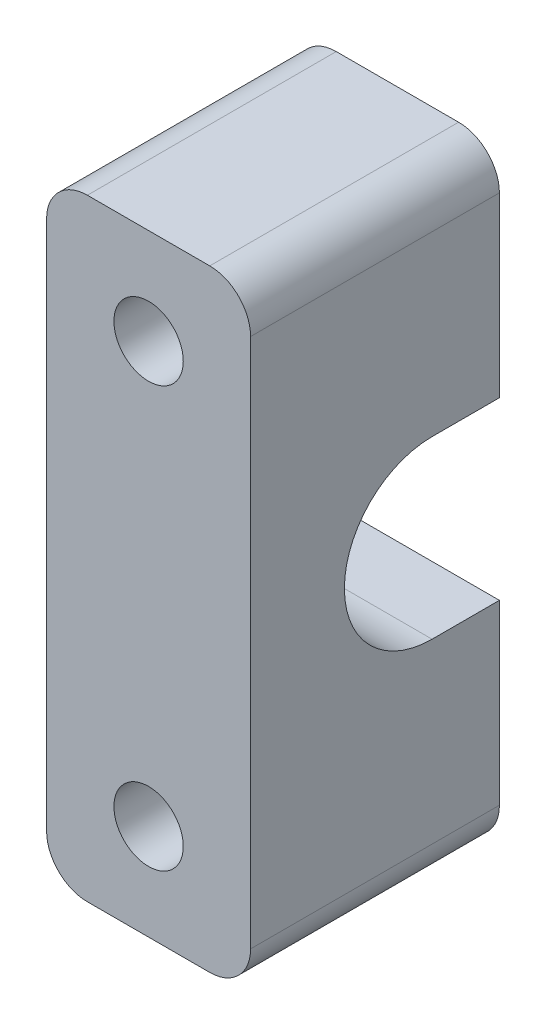
SolidWorks part; units mm, degrees
ref_plane "Front Plane" through (0, 0, 0) normal (0, 0, 1) x (1, 0, 0)
ref_plane "Top Plane" through (0, 0, 0) normal (0, 1, 0) x (1, 0, 0)
ref_plane "Right Plane" through (0, 0, 0) normal (1, 0, 0) x (0, 0, -1)
sketch "Sketch1" plane through (0, 0, 0) normal (1, 0, 0) x (0, 0, -1)
  line L1 (-6.1, -15) -> (6.1, -15)
  line L2 (-6.1, -15) -> (-6.1, 15)
  line L3 (-6.1, 15) -> (6.1, 15)
  line L4 (6.1, -15) -> (6.1, 15)
  line L5 (-6.1, -15) -> (6.1, 15) construction
  line L6 (-6.1, 15) -> (6.1, -15) construction
  point P0 (0, 0)
  dimension "D2" = 30
  dimension "D3" = 12.2
extrude "Boss-Extrude1" add sketch "Sketch1" along normal mid plane 10
sketch "Sketch5" plane through (5, 0, 0) normal (1, 0, 0) x (0, 0, -1)
  line L0 (25.0671, 0) -> (-25.0671, 0) construction
  line L1 (6.1, -15) -> (6.1, 15) construction
  circle A0 centre (2.8, 0) radius 4.3
  dimension "D1" = 8.6
  dimension "D2" = 3.3
extrude "Cut-Extrude2" cut sketch "Sketch5" against normal blind 7
sketch "Sketch3" plane through (0, 0, 6.1) normal (0, 0, 1) x (1, 0, 0)
  line L0 (0, -25.131) -> (0, 25.131) construction
  line L1 (25.0671, 0) -> (-25.0671, 0) construction
  circle A0 centre (0, 10.3) radius 1.7
  dimension "D1" = 3.4
  dimension "D2" = 10.3
extrude "Cut-Extrude1" cut sketch "Sketch3" against normal through all
mirror "Mirror1" about plane through (0, 0, 0) normal (0, 1, 0) of "Cut-Extrude1"
fillet "Fillet1" radius 2 4 edges at (-5, -15, 0) (5, -15, 0) (-5, 15, 0) (5, 15, 0)
fillet "Fillet2" radius 0.1 2 edges at (1.5, 2.7568, -6.1) (1.5, -2.7568, -6.1)
sketch "Sketch6" plane through (5, 0, 0) normal (1, 0, 0) x (0, 0, -1)
  line L0 (2.8, 0) -> (6.1, 0) construction
  line L1 (25.0671, 0) -> (-25.0671, 0) construction
  line L2 (2.8, 4.3) -> (6.1, 4.3)
  line L3 (2.8, -4.3) -> (6.1, -4.3)
  line L4 (6.1, 3.0199) -> (6.1, 13) construction
  arc A0 (2.8, 4.3) -> (2.8, -4.3) centre (2.8, 0) ccw
  arc A1 (6.1, -4.3) -> (6.1, 4.3) centre (6.1, 0) ccw
  arc A2 (5.9273, 2.9513) -> (5.9273, -2.9513) centre (2.8, 0) ccw construction
  point P5 (4.45, 0)
extrude "Cut-Extrude3" cut sketch "Sketch6" against normal up to surface (7 mm away) up to face at (-2, 0, -4.1685)
equation "\"M3_d\"= 3.4"
equation "\"rod_d\"= 8.6"
equation "\"screws_t\"= 20.6"
equation "\"t\"= 3"
equation "\"D2@Sketch1\"=\"linear_bearing_l\""
equation "\"D3@Sketch1\"=\"rod_d\" + \"t\" - \"rod_t\" + 1.6"
equation "\"linear_bearing_l\"=30"
equation "\"cover_l\"= 10"
equation "\"D1@Boss-Extrude1\"=\"cover_l\""
equation "\"D1@Sketch3\"=\"M3_d\""
equation "\"D2@Sketch3\"=\"screws_t\" / 2"
equation "\"D1@Sketch5\"=\"rod_d\""
equation "\"D2@Sketch5\"=\"rod_d\" / 2 - \"rod_t\""
equation "\"rod_t\"= 1"
equation "\"D1@Cut-Extrude2\"=\"cover_l\" - \"t\""
